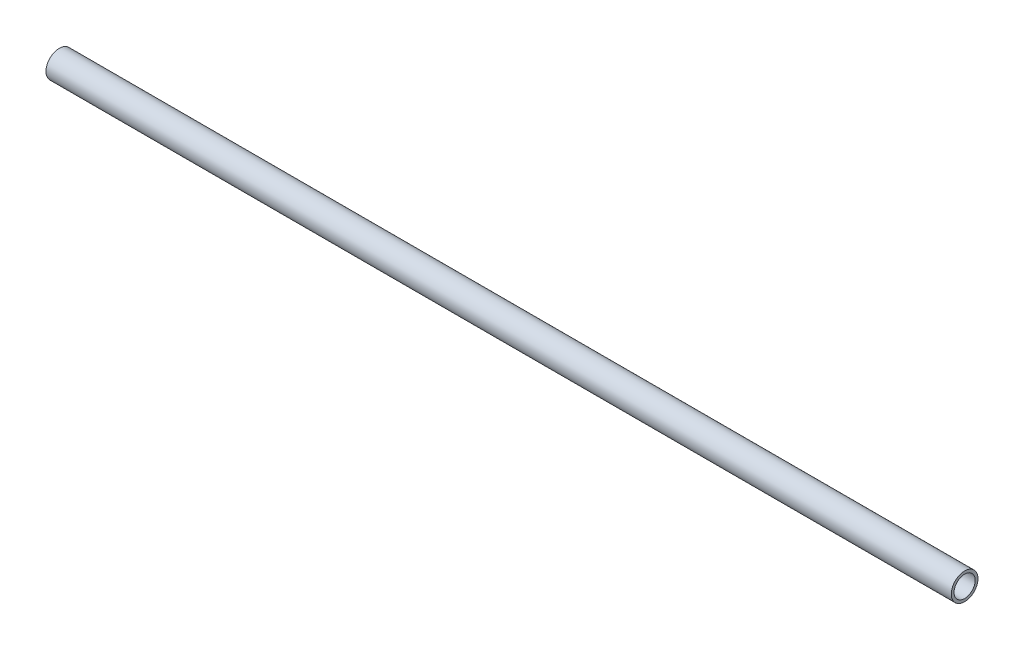
SolidWorks part; units mm, degrees
ref_plane "Front Plane" through (0, 0, 0) normal (0, 0, 1) x (1, 0, 0)
ref_plane "Top Plane" through (0, 0, 0) normal (0, 1, 0) x (1, 0, 0)
ref_plane "Right Plane" through (0, 0, 0) normal (1, 0, 0) x (0, 0, -1)
sketch "Sketch1" plane through (0, 0, 0) normal (1, 0, 0) x (0, 0, -1)
  circle A0 centre (0, 0) radius 6.2
  circle A1 centre (0, 0) radius 4.8981
  dimension "D1" = 12.4
  dimension "D2" = 9.7963
extrude "Boss-Extrude1" add sketch "Sketch1" along normal blind 420
